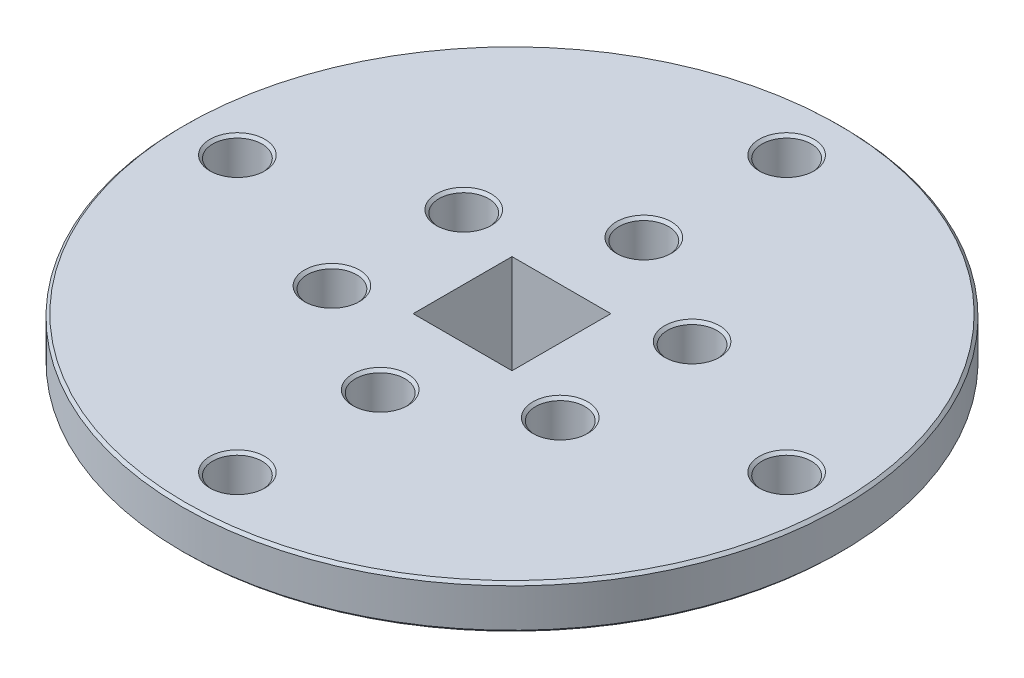
SolidWorks part; units mm, degrees
material "1.0037 (S235JR)"
ref_plane "Ebene vorne" through (0, 0, 0) normal (0, 0, 1) x (1, 0, 0)
ref_plane "Ebene oben" through (0, 0, 0) normal (0, 1, 0) x (1, 0, 0)
ref_plane "Ebene rechts" through (0, 0, 0) normal (1, 0, 0) x (0, 0, -1)
sketch "Skizze1" plane through (0, 0, 0) normal (0, 1, 0) x (1, 0, 0)
  circle A1 centre (0, 0) radius 20.5
  dimension "D2" = 41
extrude "Aufsatz-Linear austragen1" add sketch "Skizze1" along normal blind 5
sketch "Skizze3" plane through (0, 5, 0) normal (0, 1, 0) x (1, 0, 0)
  circle A1 centre (0, 0) radius 30
  dimension "D1" = 60
extrude "Aufsatz-Linear austragen2" add sketch "Skizze3" along normal blind 4
hole_wizard "Durchgangsloch für M41" positions "Skizze4" profile "Skizze5" hole size "M4" standard "ANSI Metrisch" end condition through all
sketch "Skizze4" plane through (0, 5, 0) normal (0, -1, 0) x (-1, 0, 0)
  circle A0 centre (0, 0) radius 25 construction
  point P0 (0, 25)
  point P8 (-25, 0)
  point P10 (0, -25)
  point P12 (25, 0)
  dimension "D1" = 50
sketch "Skizze5" plane through (0, 5, -25) normal (1, 0, 0) x (0, 0, -1)
  line L0 (0, 0) -> (0, 4)
  line L1 (0, 4) -> (2.25, 4)
  line L2 (2.25, 4) -> (2.25, 0)
  line L5 (2.25, 0) -> (0, 0)
  line L11 (0, -6.35) -> (0, 107.95) construction
  dimension "Bohrerdurchmesser" = 4.5
  dimension "Bohrungstiefe" = 4
hole_wizard "Durchgangsloch für M42" positions "Skizze7" profile "Skizze8" hole size "M4" standard "DIN" end condition through all
sketch "Skizze7" plane through (0, 9, 0) normal (0, 1, 0) x (1, 0, 0)
  circle A0 centre (0, 0) radius 12 construction
  point P5 (0, 12)
  point P12 (10.3923, 6)
  point P13 (10.3923, -6)
  point P14 (0, -12)
  point P15 (-10.3923, -6)
  point P16 (-10.3923, 6)
  dimension "D1" = 24
  dimension "D2" = 6
sketch "Skizze8" plane through (-10.3923, 9, -6) normal (1, 0, 0) x (0, 0, 1)
  line L0 (0, 0) -> (0, 9)
  line L1 (0, 9) -> (2.25, 9)
  line L2 (2.25, 9) -> (2.25, 0)
  line L5 (2.25, 0) -> (0, 0)
  line L11 (0, -6.35) -> (0, 107.95) construction
  dimension "Bohrerdurchmesser" = 4.5
  dimension "Bohrungstiefe" = 9
sketch "Skizze9" plane through (0, 0, 0) normal (0, -1, 0) x (1, 0, 0)
  line L1 (-4.5, -4.5) -> (4.5, -4.5)
  line L2 (-4.5, -4.5) -> (-4.5, 4.5)
  line L3 (-4.5, 4.5) -> (4.5, 4.5)
  line L4 (4.5, -4.5) -> (4.5, 4.5)
  line L5 (-4.5, -4.5) -> (4.5, 4.5) construction
  line L6 (-4.5, 4.5) -> (4.5, -4.5) construction
  point P0 (0, 0)
  dimension "D1" = 9
extrude "Schnitt-Linear austragen1" cut sketch "Skizze9" against normal up to next
chamfer "Fase1" distance 0.25 angle 45 23 edges at (0, 9, -9.75) (0, 0, -9.75) (10.3923, 9, -3.75) (10.3923, 0, -3.75) (10.3923, 9, 8.25) (10.3923, 0, 8.25) (0, 9, 14.25) (0, 0, 14.25) (-10.3923, 9, 8.25) (-10.3923, 0, 8.25) (-10.3923, 9, -3.75) (-10.3923, 0, -3.75) (0, 5, -27.25) (0, 9, -27.25) (25, 5, -2.25) (25, 9, -2.25) (0, 5, 22.75) (0, 9, 22.75) (-25, 5, -2.25) (-25, 9, -2.25) (0, 9, 30) (0, 0, 20.5) (0, 5, 30)
